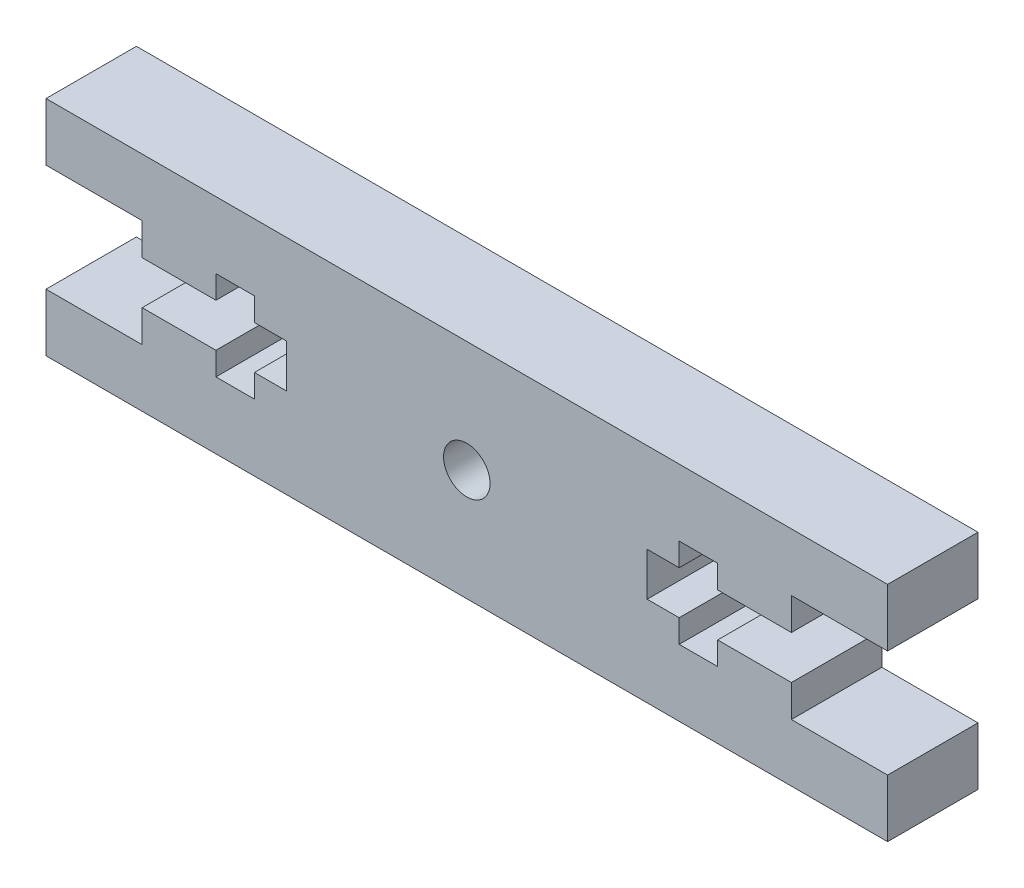
SolidWorks part; units mm, degrees
material "Acrylic (Medium-high impact)"
ref_plane "Front Plane" through (0, 0, 0) normal (0, 0, 1) x (1, 0, 0)
ref_plane "Top Plane" through (0, 0, 0) normal (0, 1, 0) x (1, 0, 0)
ref_plane "Right Plane" through (0, 0, 0) normal (1, 0, 0) x (0, 0, -1)
sketch "Sketch1" plane through (0, 0, 0) normal (0, 0, 1) x (1, 0, 0)
  line L0 (727.3394, 352.6063) -> (779.8394, 352.6063)
  line L1 (753.5894, -654.3154) -> (753.5894, 49345.6846) construction
  line L2 (742.3394, 347.0063) -> (742.3394, 344.3063)
  line L3 (727.3394, 349.0063) -> (733.3394, 349.0063)
  line L4 (733.3394, 349.0063) -> (733.3394, 347.0063)
  line L5 (733.3394, 347.0063) -> (737.9394, 347.0063)
  line L6 (737.9394, 348.4463) -> (740.3394, 348.4463)
  line L7 (-245.8122, 345.6563) -> (49754.1878, 345.6563) construction
  line L8 (727.3394, 338.7063) -> (727.3394, 342.3063)
  line L9 (737.9394, 344.3063) -> (737.9394, 342.8663)
  line L10 (740.3394, 342.8663) -> (740.3394, 344.3063)
  line L11 (740.3394, 344.3063) -> (742.3394, 344.3063)
  line L12 (737.9394, 342.8663) -> (740.3394, 342.8663)
  line L13 (733.3394, 344.3063) -> (737.9394, 344.3063)
  line L14 (740.3394, 347.0063) -> (742.3394, 347.0063)
  line L15 (740.3394, 348.4463) -> (740.3394, 347.0063)
  line L16 (733.3394, 342.3063) -> (733.3394, 344.3063)
  line L17 (737.9394, 347.0063) -> (737.9394, 348.4463)
  line L18 (727.3394, 342.3063) -> (733.3394, 342.3063)
  line L19 (727.3394, 338.7063) -> (779.8394, 338.7063)
  line L20 (779.8394, 352.6063) -> (779.8394, 349.0063)
  line L21 (779.8394, 342.3063) -> (773.8394, 342.3063)
  line L22 (769.2394, 347.0063) -> (769.2394, 348.4463)
  line L23 (773.8394, 342.3063) -> (773.8394, 344.3063)
  line L24 (766.8394, 348.4463) -> (766.8394, 347.0063)
  line L25 (766.8394, 347.0063) -> (764.8394, 347.0063)
  line L26 (773.8394, 344.3063) -> (769.2394, 344.3063)
  line L27 (769.2394, 342.8663) -> (766.8394, 342.8663)
  line L28 (766.8394, 344.3063) -> (764.8394, 344.3063)
  line L29 (766.8394, 342.8663) -> (766.8394, 344.3063)
  line L30 (769.2394, 344.3063) -> (769.2394, 342.8663)
  line L31 (779.8394, 338.7063) -> (779.8394, 342.3063)
  line L32 (769.2394, 348.4463) -> (766.8394, 348.4463)
  line L33 (773.8394, 347.0063) -> (769.2394, 347.0063)
  line L34 (727.3394, 352.6063) -> (727.3394, 349.0063)
  line L35 (773.8394, 349.0063) -> (773.8394, 347.0063)
  line L36 (779.8394, 349.0063) -> (773.8394, 349.0063)
  line L37 (764.8394, 347.0063) -> (764.8394, 344.3063)
  circle A0 centre (753.5894, 345.6563) radius 1.45
  point P7 (753.5894, 352.6063)
  point P8 (764.8394, 345.6563)
  point P24 (742.3394, 345.6563)
  point P28 (753.5894, 338.7063)
  point P46 (753.5894, 352.6063)
  dimension "D1" = 3.6
  dimension "D10" = 2.9
  dimension "D2" = 4.6
  dimension "D3" = 6
  dimension "D4" = 1.44
  dimension "D5" = 2.4
  dimension "D6" = 2
  dimension "D7" = 2
  dimension "D8" = 40.5
  dimension "D9" = 2.7
extrude "Boss-Extrude2" add sketch "Sketch1" along normal blind 5.64
